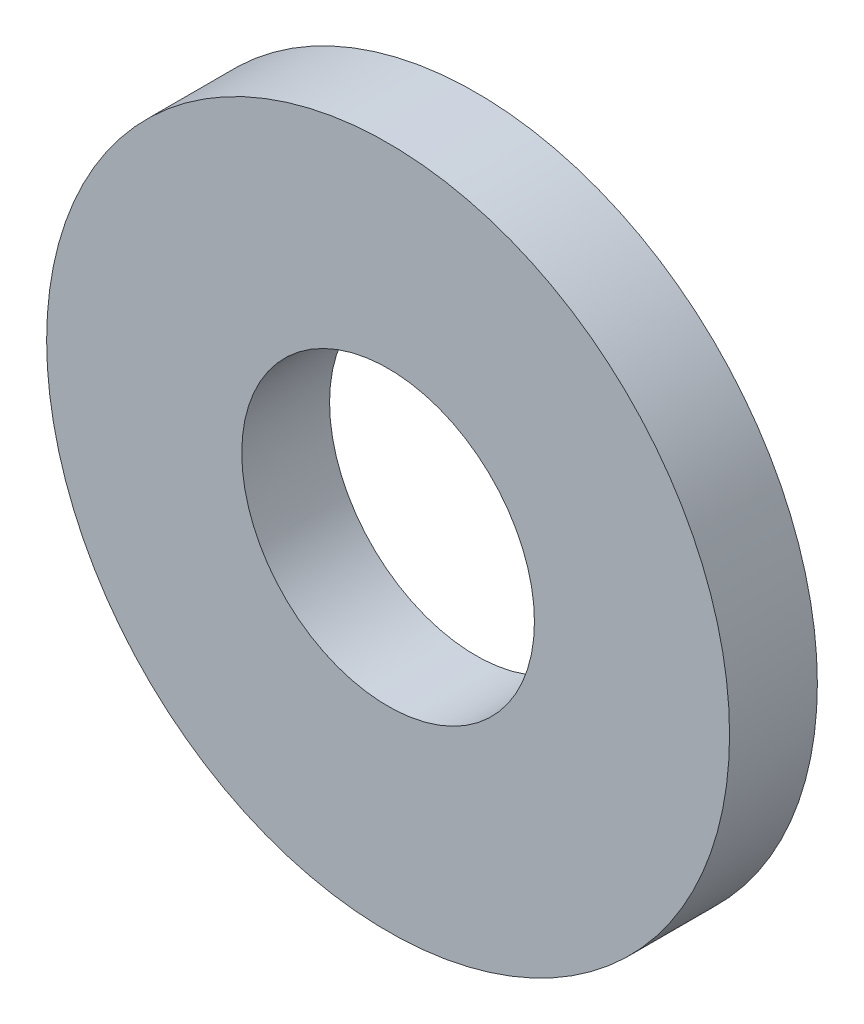
SolidWorks part; units mm, degrees
ref_plane "Front Plane" through (0, 0, 0) normal (0, 0, 1) x (1, 0, 0)
ref_plane "Top Plane" through (0, 0, 0) normal (0, 1, 0) x (1, 0, 0)
ref_plane "Right Plane" through (0, 0, 0) normal (1, 0, 0) x (0, 0, -1)
sketch "Sketch1" plane through (0, 0, 0) normal (0, 0, 1) x (1, 0, 0)
  circle A0 centre (0, 0) radius 3.556
  circle A1 centre (0, 0) radius 1.524
  point P5 (0, -3.556)
  dimension "OD" = 7.112
  dimension "ID" = 3.048
sketch "Sketch2" plane through (0, 0, 0) normal (1, 0, 0) x (0, 0, -1)
  line L0 (-0.4572, 0) -> (0.4572, 0) construction
  point P0 (-0.4572, -3.556)
  point P4 (0, 0)
  point P6 (0.4572, -3.556)
  dimension "Thickness Range" = 0.9144
sketch "Sketch3" plane through (0, 0, 0) normal (0, 0, 1) x (1, 0, 0)
  circle A0 centre (0, 0) radius 3.556 construction
  circle A1 centre (0, 0) radius 1.524 construction
  circle A2 centre (0, 0) radius 3.556
  circle A3 centre (0, 0) radius 1.524
extrude "Boss-Extrude1" add sketch "Sketch3" along normal up to vertex (0.4572 mm away) and the other way up to vertex (0.4572 mm away) up to point (0, -3.556, 0.4572) other way up to point (0, -3.556, -0.4572)
